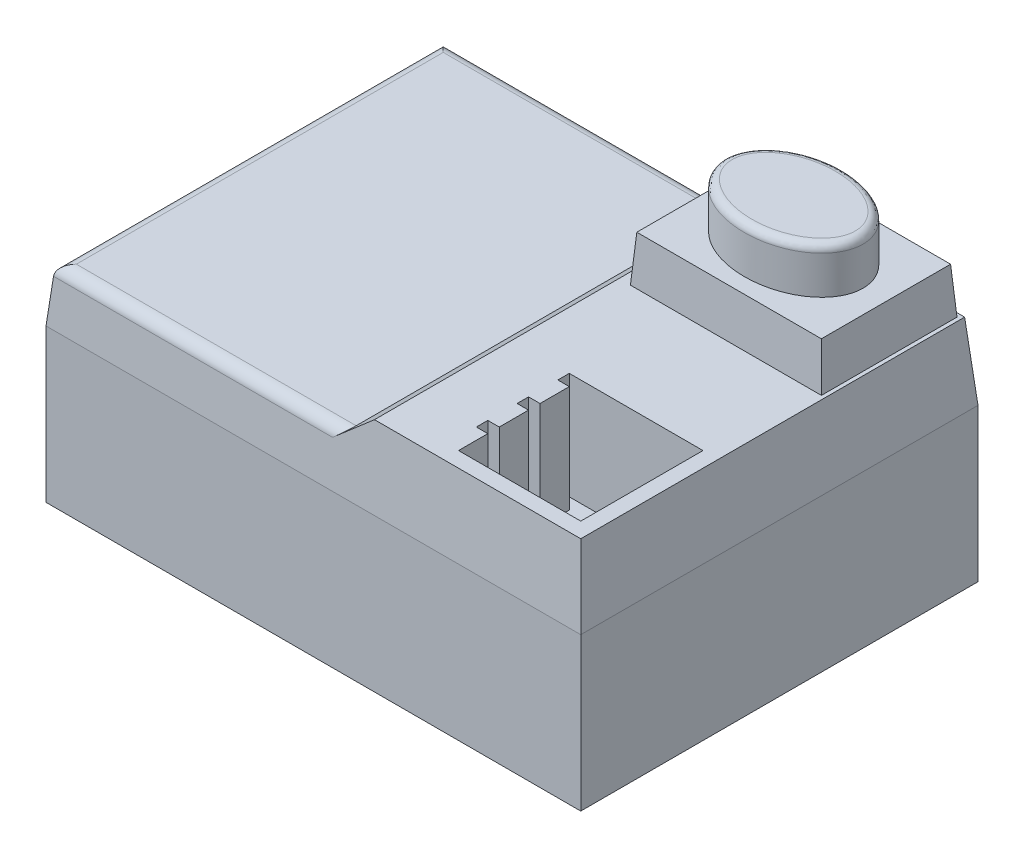
SolidWorks part; units mm, degrees
ref_plane "Front Plane" through (0, 0, 0) normal (0, 0, 1) x (1, 0, 0)
ref_plane "Top Plane" through (0, 0, 0) normal (0, 1, 0) x (1, 0, 0)
ref_plane "Right Plane" through (0, 0, 0) normal (1, 0, 0) x (0, 0, -1)
sketch "Sketch1" plane through (0, 0, 0) normal (0, 1, 0) x (1, 0, 0)
  line L1 (-17.5, -13) -> (17.5, -13)
  line L2 (-17.5, -13) -> (-17.5, 13)
  line L3 (-17.5, 13) -> (17.5, 13)
  line L4 (17.5, -13) -> (17.5, 13)
  line L5 (-17.5, -13) -> (17.5, 13) construction
  line L6 (-17.5, 13) -> (17.5, -13) construction
  point P0 (0, 0)
  dimension "D1" = 35
  dimension "D2" = 26
extrude "Boss-Extrude1" add sketch "Sketch1" along normal blind 10
sketch "Sketch2" plane through (0, 10, 0) normal (0, 1, 0) x (1, 0, 0)
  line L1 (-17.5, -13) -> (17.5, -13)
  line L2 (-17.5, -13) -> (-17.5, 13)
  line L3 (-17.5, 13) -> (17.5, 13)
  line L4 (17.5, -13) -> (17.5, 13)
  line L5 (-17.5, -13) -> (17.5, 13) construction
  line L6 (-17.5, 13) -> (17.5, -13) construction
  line L8 (17.5, 13) -> (-17.5, 13) construction
  line L9 (17.5, -13) -> (17.5, 13) construction
  point P0 (0, 0)
extrude "Boss-Extrude3" add sketch "Sketch2" along normal blind 5 draft 5
sketch "Sketch3" plane through (0, 0, 13) normal (0, 0, 1) x (1, 0, 0)
  line L0 (3.5626, 15) -> (1.8062, 13.5)
  line L1 (-17.0626, 15) -> (17.0626, 15) construction
  line L2 (1.8062, 13.5) -> (-17.5009, 13.5)
  line L3 (-17.5009, 13.5) -> (-17.5009, 15)
  line L4 (-17.5009, 15) -> (3.5626, 15)
  line L6 (-17.0626, 15) -> (-17.5, 10) construction
  point P4 (-17.1938, 13.5)
  point P7 (-17.1938, 13.5)
  dimension "D1" = 1.5
  dimension "D2" = 13.5
  dimension "D3" = 19
extrude "Cut-Extrude1" cut sketch "Sketch3" against normal through all contours L4 L3 L2 L0
sketch "Sketch4" plane through (0, 15, 0) normal (0, 1, 0) x (1, 0, 0)
  line L0 (8.0626, -6.2292) -> (8.0626, -4.3126)
  line L1 (8.0626, -11.5626) -> (16.0626, -11.5626)
  line L2 (8.0626, -11.5626) -> (8.0626, -9.6459)
  line L3 (8.0626, -3.5626) -> (16.0626, -3.5626)
  line L4 (16.0626, -11.5626) -> (16.0626, -3.5626)
  line L5 (8.0626, -8.8959) -> (8.0626, -6.9792)
  line L6 (3.5626, -12.5626) -> (17.0626, -12.5626) construction
  line L7 (17.0626, -12.5626) -> (17.0626, 12.5626) construction
  line L8 (8.0626, -3.5626) -> (7.3126, -3.5626)
  line L9 (7.3126, -3.5626) -> (7.3126, -4.3126)
  line L10 (7.3126, -4.3126) -> (8.0626, -4.3126)
  line L11 (8.0626, -6.2292) -> (7.3126, -6.2292)
  line L12 (7.3126, -6.2292) -> (7.3126, -6.9792)
  line L13 (7.3126, -6.9792) -> (8.0626, -6.9792)
  line L14 (8.0626, -9.6459) -> (7.3126, -9.6459)
  line L15 (7.3126, -9.6459) -> (7.3126, -8.8959)
  line L16 (7.3126, -8.8959) -> (8.0626, -8.8959)
  point P17 (0, 0)
  dimension "D1" = 1
  dimension "D2" = 1
  dimension "D3" = 8
  dimension "D4" = 8
  dimension "D5" = 0.75
  dimension "D6" = 0.75
  dimension "D7" = 1.9167
  dimension "D8" = 0.75
  dimension "D9" = 1.9167
  dimension "D10" = 0.75
  dimension "D11" = 1.9167
  dimension "D12" = 8
extrude "Cut-Extrude2" cut sketch "Sketch4" against normal blind 7
sketch "Sketch5" plane through (0, 15, 0) normal (0, 1, 0) x (1, 0, 0)
  line L0 (17.0626, 12.5626) -> (3.5626, 12.5626) construction
  line L1 (4.3126, 12.3126) -> (16.8126, 12.3126)
  line L2 (4.3126, 12.3126) -> (4.3126, 3.4374)
  line L3 (4.3126, 3.4374) -> (16.8126, 3.4374)
  line L4 (16.8126, 12.3126) -> (16.8126, 3.4374)
  line L5 (17.0626, -12.5626) -> (17.0626, 12.5626) construction
  line L6 (3.5626, -12.5626) -> (3.5626, 12.5626) construction
  line L7 (3.5626, -12.5626) -> (17.0626, -12.5626) construction
  dimension "D1" = 0.25
  dimension "D2" = 0.25
  dimension "D3" = 0.75
  dimension "D4" = 16
extrude "Boss-Extrude4" add sketch "Sketch5" along normal blind 3 draft 4
sketch "Sketch6" plane through (0, 18, 0) normal (0, 1, 0) x (1, 0, 0)
  line L0 (16.6028, 12.1028) -> (4.5223, 12.1028) construction
  line L1 (4.5223, 3.6472) -> (16.6028, 3.6472) construction
  line L2 (15.1028, 7.875) -> (10.5626, 7.875) construction
  line L3 (16.6028, 3.6472) -> (16.6028, 12.1028) construction
  line L4 (4.5223, 12.1028) -> (4.5223, 3.6472) construction
  ellipse E0 centre (10.5626, 7.875) end of major axis (15.1028, 7.875) minor radius 3.2278
  point P11 (4.9019, 7.6852)
  point P12 (0, 0)
  point P15 (5.5578, 7.875)
  dimension "D1" = 1
  dimension "D2" = 1
  dimension "D3" = 1.5
  dimension "D4" = 1.5
extrude "Boss-Extrude5" add sketch "Sketch6" along normal blind 3
fillet "Fillet1" radius 0.5 1 edges at (15.1028, 21, -7.875)
fillet "Fillet2" radius 0.75 3 edges at (-7.6938, 13.5, 12.6938) (-17.1938, 13.5, 0) (-7.6938, 13.5, -12.6938)
